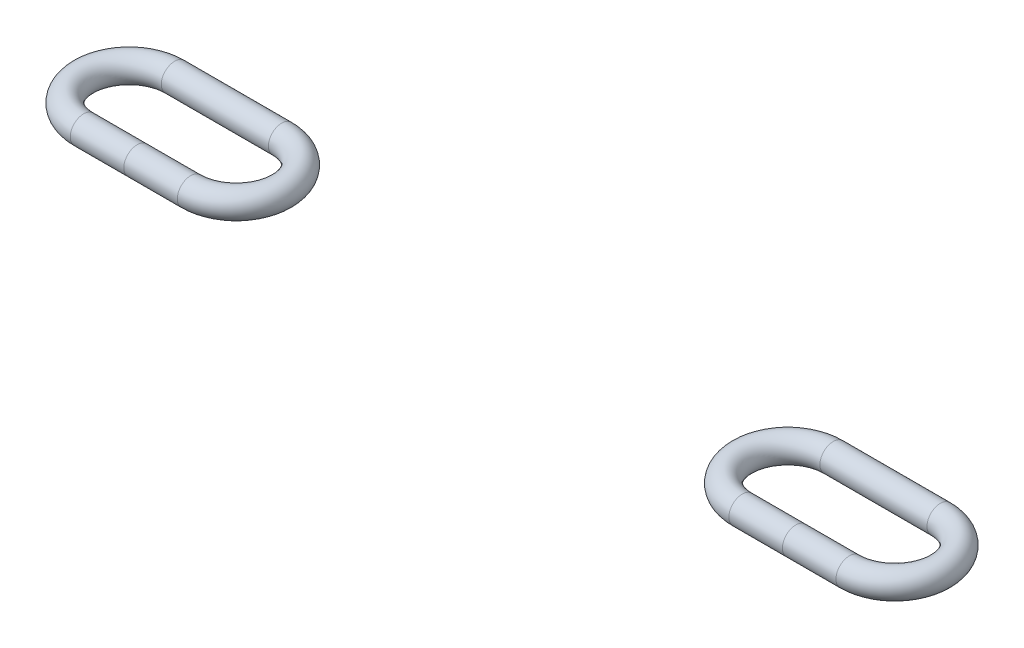
SolidWorks part; units mm, degrees
ref_plane "前视基准面" through (0, 0, 0) normal (0, 0, 1) x (1, 0, 0)
ref_plane "上视基准面" through (0, 0, 0) normal (0, 1, 0) x (1, 0, 0)
ref_plane "右视基准面" through (0, 0, 0) normal (1, 0, 0) x (0, 0, -1)
sketch "草图1" plane through (0, 0, 0) normal (0, 1, 0) x (1, 0, 0)
  line L0 (-1, 0) -> (1, 0) construction
  line L1 (-1, 0.85) -> (1, 0.85)
  line L2 (-1, -0.85) -> (1, -0.85)
  arc A0 (-1, 0.85) -> (-1, -0.85) centre (-1, 0) ccw
  arc A1 (1, -0.85) -> (1, 0.85) centre (1, 0) ccw
  point P2 (0, 0)
sketch "草图2" plane through (0, 0, 0) normal (1, 0, 0) x (0, 0, -1)
  line L0 (0.85, 0) -> (-0.85, 0) construction
  line L1 (0.85, 0) -> (-0.85, 0) construction
  circle A0 centre (-0.85, 0) radius 0.25
  point P4 (-1.2, 0)
  point P7 (0, 0)
sweep "扫描1" add profiles "草图2" path "草图1"
ref_plane "基准面4" through (-6.15, 0, 0) normal (1, 0, 0) x (0, 0, -1)
mirror "镜向3" about plane through (-6.15, 0, 0) normal (1, 0, 0) of bodies 101
